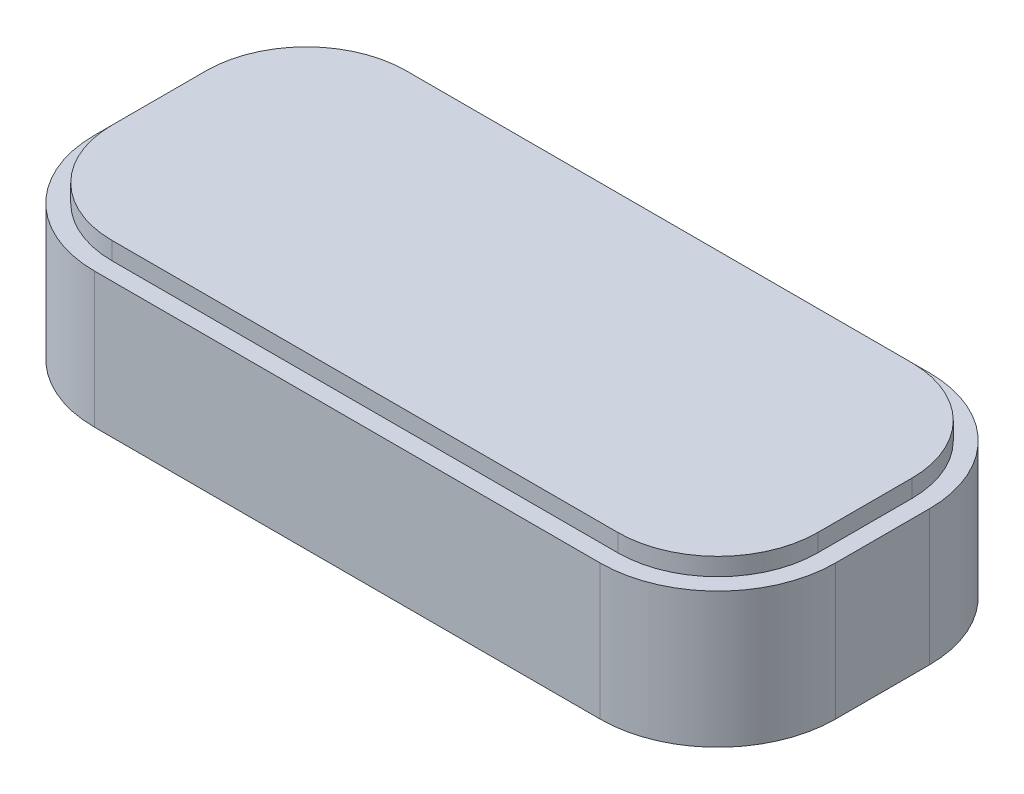
SolidWorks part; units mm, degrees
ref_plane "Front Plane" through (0, 0, 0) normal (0, 0, 1) x (1, 0, 0)
ref_plane "Top Plane" through (0, 0, 0) normal (0, 1, 0) x (1, 0, 0)
ref_plane "Right Plane" through (0, 0, 0) normal (1, 0, 0) x (0, 0, -1)
sketch "Sketch1" plane through (0, 0, 0) normal (0, 1, 0) x (1, 0, 0)
  line L0 (-1.6002, 0.2032) -> (-1.6002, -0.2032)
  line L1 (-1.6002, 0.7112) -> (1.6002, 0.7112) construction
  line L2 (-1.6002, 0.7112) -> (-1.6002, -0.7112) construction
  line L3 (-1.6002, -0.7112) -> (1.6002, -0.7112) construction
  line L4 (1.6002, 0.7112) -> (1.6002, -0.7112) construction
  line L5 (-1.0922, -0.7112) -> (1.0922, -0.7112)
  line L6 (-1.0922, 0.7112) -> (1.0922, 0.7112)
  line L7 (1.6002, -0.2032) -> (1.6002, 0.2032)
  arc A0 (-1.6002, 0.2032) -> (-1.0922, 0.7112) centre (-1.0922, 0.2032) cw
  arc A1 (-1.6002, -0.2032) -> (-1.0922, -0.7112) centre (-1.0922, -0.2032) ccw
  arc A2 (1.0922, -0.7112) -> (1.6002, -0.2032) centre (1.0922, -0.2032) ccw
  arc A3 (1.6002, 0.2032) -> (1.0922, 0.7112) centre (1.0922, 0.2032) ccw
  point P4 (-1.6002, 0)
  point P6 (0, 0.7112)
  dimension "D3" = 0.508
  dimension "D1" = 3.2004
  dimension "D2" = 1.4224
extrude "Boss-Extrude1" add sketch "Sketch1" along normal blind 0.5842
sketch "Sketch2" plane through (0, 0.5842, 0) normal (0, 1, 0) x (1, 0, 0)
  line L0 (-1.524, 0.2032) -> (-1.524, -0.2032)
  line L1 (-1.0922, -0.635) -> (1.0922, -0.635)
  line L2 (1.524, -0.2032) -> (1.524, 0.2032)
  line L3 (1.0922, 0.635) -> (-1.0922, 0.635)
  line L4 (1.6002, -0.2032) -> (1.6002, 0.2032) construction
  line L5 (1.0922, 0.7112) -> (-1.0922, 0.7112) construction
  arc A0 (-1.524, 0.2032) -> (-1.0922, 0.635) centre (-1.0922, 0.2032) cw
  arc A1 (-1.0922, 0.7112) -> (-1.6002, 0.2032) centre (-1.0922, 0.2032) ccw construction
  arc A2 (-1.524, -0.2032) -> (-1.0922, -0.635) centre (-1.0922, -0.2032) ccw
  arc A3 (1.0922, -0.635) -> (1.524, -0.2032) centre (1.0922, -0.2032) ccw
  arc A4 (1.524, 0.2032) -> (1.0922, 0.635) centre (1.0922, 0.2032) ccw
  arc A5 (1.6002, 0.2032) -> (1.0922, 0.7112) centre (1.0922, 0.2032) ccw construction
  arc A6 (1.0922, -0.7112) -> (1.6002, -0.2032) centre (1.0922, -0.2032) ccw construction
  arc A7 (-1.6002, -0.2032) -> (-1.0922, -0.7112) centre (-1.0922, -0.2032) ccw construction
  point P25 (1.524, 0)
  point P28 (1.6002, 0)
  point P29 (0, 0.635)
  point P32 (0, 0.7112)
  dimension "D1" = 0.0762
extrude "Boss-Extrude2" add sketch "Sketch2" along normal blind 0.0762
sketch "Sketch3" plane through (0, 0.6604, 0) normal (0, 1, 0) x (1, 0, 0)
  line L0 (-1.1349, -0.3449) -> (1.1255, -0.3449) construction
